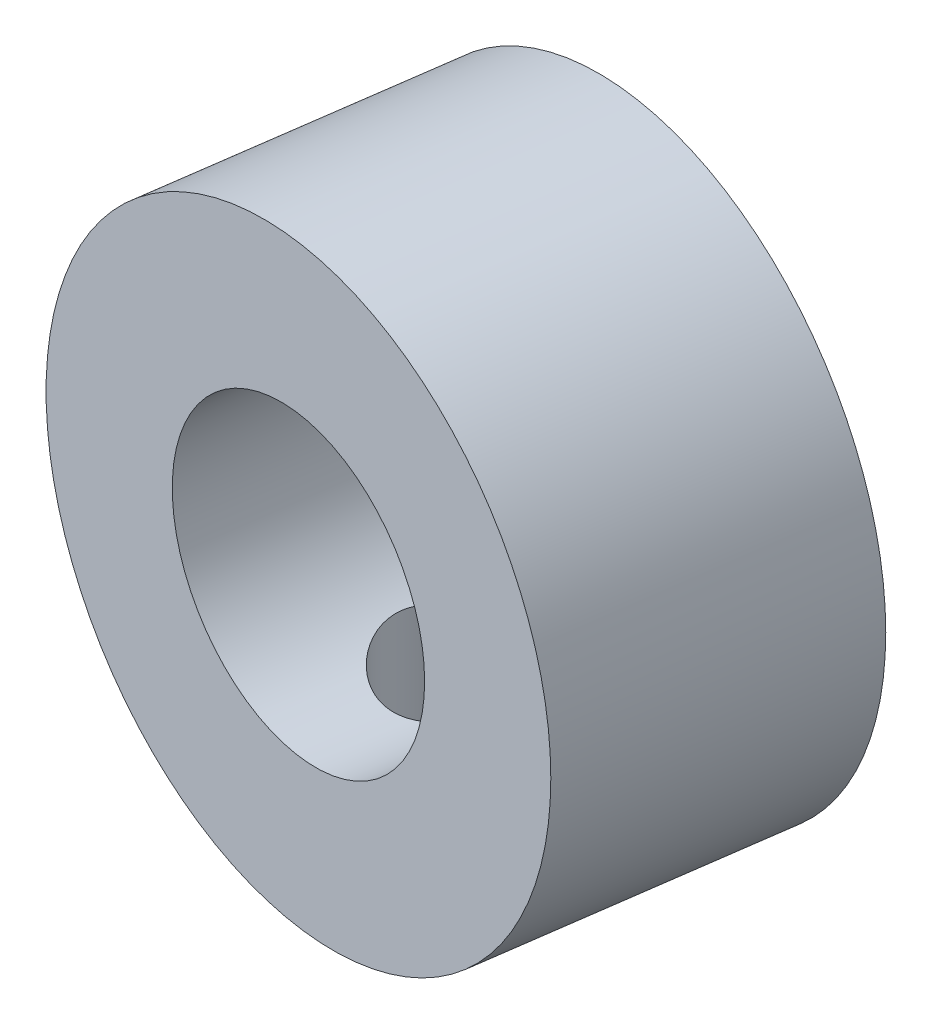
SolidWorks part; units mm, degrees
ref_plane "Front Plane" through (0, 0, 0) normal (0, 0, 1) x (1, 0, 0)
ref_plane "Top Plane" through (0, 0, 0) normal (0, 1, 0) x (1, 0, 0)
ref_plane "Right Plane" through (0, 0, 0) normal (1, 0, 0) x (0, 0, -1)
sketch "Sketch1" plane through (-29.9585, -0.0055, 37.9225) normal (0.9894, -0.0409, 0.1391) x (0.1393, 0, -0.9903)
  line L0 (22.0768, -6.5301) -> (73.3766, -6.5301) construction
  line L1 (50.2159, -0.1801) -> (56.5659, -0.1801) construction
  line L2 (50.2159, -0.1801) -> (50.2159, -12.8801) construction
  line L3 (50.2159, -12.8801) -> (56.5659, -12.8801) construction
  line L4 (56.5659, -0.1801) -> (56.5659, -12.8801) construction
  line L5 (50.2159, -6.5301) -> (56.5659, -6.5301)
  line L6 (50.2159, -0.1801) -> (56.5659, -0.1801)
  line L7 (50.2159, -9.7051) -> (50.2159, -12.8801)
  line L8 (50.2159, -12.8801) -> (56.5659, -12.8801)
  line L9 (56.5659, -9.7051) -> (56.5659, -12.8801)
  line L10 (38.8875, -9.7051) -> (56.5659, -9.7051) construction
  line L11 (50.2159, -9.7051) -> (56.5659, -9.7051)
revolve "Revolve1" add sketch "Sketch1" angle 360 about L5
ref_plane "Plane1" through (0, -12.8801, 0) normal (0, -1, 0) x (-1, 0, 0)
sketch "Sketch2" plane through (0, -12.8801, 0) normal (0, -1, 0) x (-1, 0, 0)
  line L0 (23.4876, 11.8775) -> (22.6034, 18.1657) construction
  line L1 (23.4876, 11.8775) -> (22.6034, 18.1657)
  point P2 (23.0455, 15.0216)
hole_wizard "#6-32 Tapped Hole1" positions "Sketch4" profile "Sketch5" tap size "#6-32" standard "ANSI Inch"
sketch "Sketch4" plane through (0, -12.8801, 0) normal (0, -1, 0) x (-1, 0, 0)
  point P0 (23.0455, 15.0216)
sketch "Sketch5" plane through (-23.0455, -12.8801, -15.0216) normal (1, 0, 0) x (0, 0, -1)
  line L0 (0, 0) -> (0, 7.1627)
  line L1 (0, 7.1627) -> (1.3525, 6.35)
  line L2 (1.3525, 6.35) -> (1.3525, 0)
  line L5 (1.3525, 0) -> (0, 0)
  line L10 (0, 7.1627) -> (-1.3526, 6.35) construction
  line L11 (0, -6.35) -> (0, 107.95) construction
  dimension "Tap Drill Dia." = 2.7051
  dimension "Tap Drill Depth" = 6.35
  dimension "Drill Angle" = 118
cosmetic thread "Hole Thread1" parameters "D1"=3.4775, "D2"=3.5052
